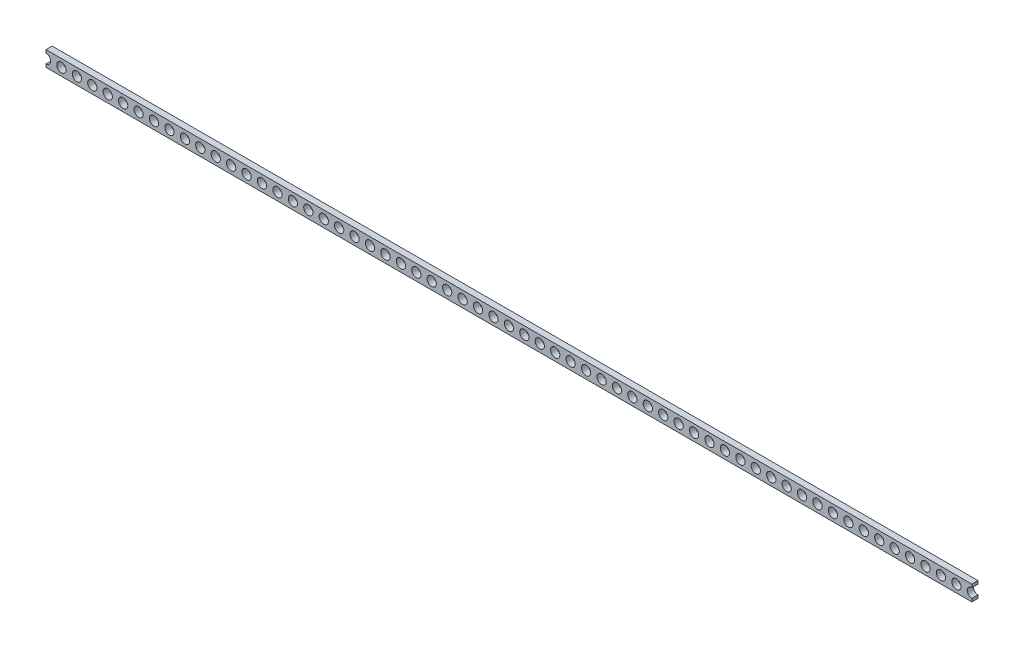
SolidWorks part; units mm, degrees
ref_plane "前视基准面" through (0, 0, 0) normal (0, 0, 1) x (1, 0, 0)
ref_plane "上视基准面" through (0, 0, 0) normal (0, 1, 0) x (1, 0, 0)
ref_plane "右视基准面" through (0, 0, 0) normal (1, 0, 0) x (0, 0, -1)
sketch "草图1" plane through (0, 0, 0) normal (0, 0, 1) x (1, 0, 0)
  line L1 (0, 0) -> (300, 0)
  line L2 (0, 0) -> (0, -5)
  line L3 (0, -5) -> (300, -5)
  line L4 (300, 0) -> (300, -5)
  dimension "D1" = 5
  dimension "D2" = 300
extrude "凸台-拉伸1" add sketch "草图1" along normal blind 2
sketch "草图2" plane through (0, 0, 2) normal (0, 0, 1) x (1, 0, 0)
  line L0 (300, 0) -> (0, 0) construction
  line L1 (150, 0) -> (150, -5) construction
  line L2 (0, -5) -> (300, -5) construction
  circle A0 centre (150, -2.5) radius 1.5
  dimension "D1" = 3
extrude "切除-拉伸1" cut sketch "草图2" against normal through all
pattern_linear "阵列(线性)1" count 41 spacing 5 along (1, 0, 0) of "切除-拉伸1"
pattern_linear "阵列(线性)2" count 41 spacing 5 along (-1, 0, 0) of "切除-拉伸1"
